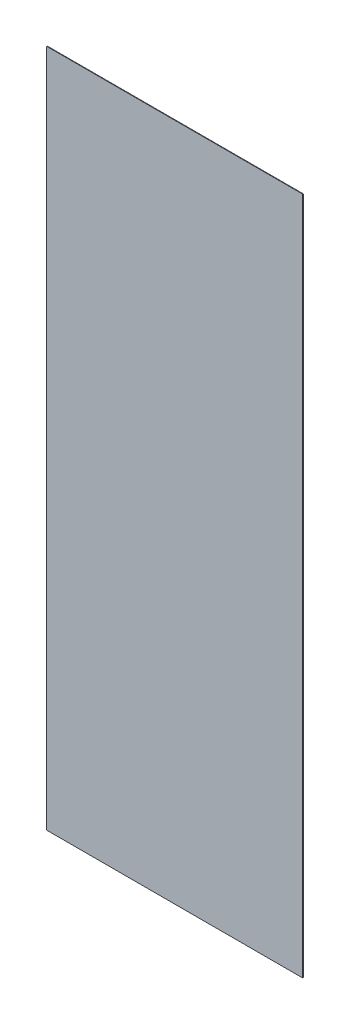
SolidWorks part; units mm, degrees
ref_plane "Front Plane" through (0, 0, 0) normal (0, 0, 1) x (1, 0, 0)
ref_plane "Top Plane" through (0, 0, 0) normal (0, 1, 0) x (1, 0, 0)
ref_plane "Right Plane" through (0, 0, 0) normal (1, 0, 0) x (0, 0, -1)
other "Configuration Table"
sketch "Sketch1" plane through (0, 0, 0) normal (0, 0, 1) x (1, 0, 0)
  line L1 (1.5, 120) -> (698.5, 120)
  line L2 (1.5, 120) -> (1.5, 1968.5)
  line L3 (1.5, 1968.5) -> (698.5, 1968.5)
  line L4 (698.5, 120) -> (698.5, 1968.5)
extrude "PACK_dis_arka_1" add sketch "Sketch1" against normal blind 1.5 from offset 818.5 separate body
